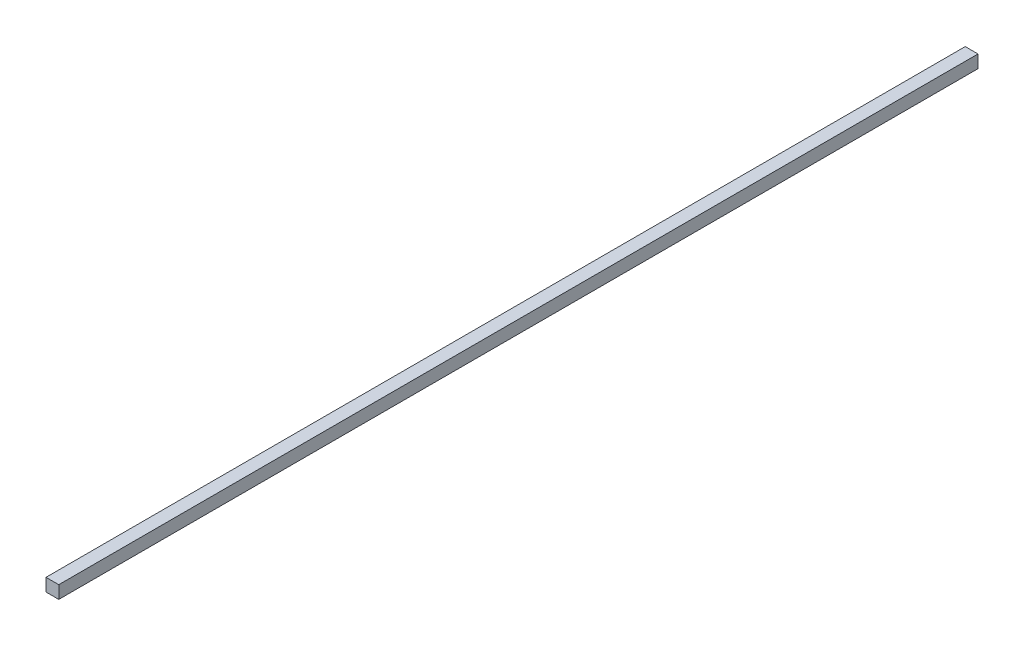
SolidWorks part; units mm, degrees
ref_plane "Front Plane" through (0, 0, 0) normal (0, 0, 1) x (1, 0, 0)
ref_plane "Top Plane" through (0, 0, 0) normal (0, 1, 0) x (1, 0, 0)
ref_plane "Right Plane" through (0, 0, 0) normal (1, 0, 0) x (0, 0, -1)
sketch "Sketch1" plane through (0, 0, 0) normal (0, 0, 1) x (1, 0, 0)
  line L1 (0, 0) -> (25.4, 0)
  line L2 (0, 0) -> (0, 25.4)
  line L3 (0, 25.4) -> (25.4, 25.4)
  line L4 (25.4, 0) -> (25.4, 25.4)
  dimension "D1" = 25.4
  dimension "D2" = 25.4
extrude "Boss-Extrude1" add sketch "Sketch1" along normal blind 1828.8 contours L3 L4 L1 L2
